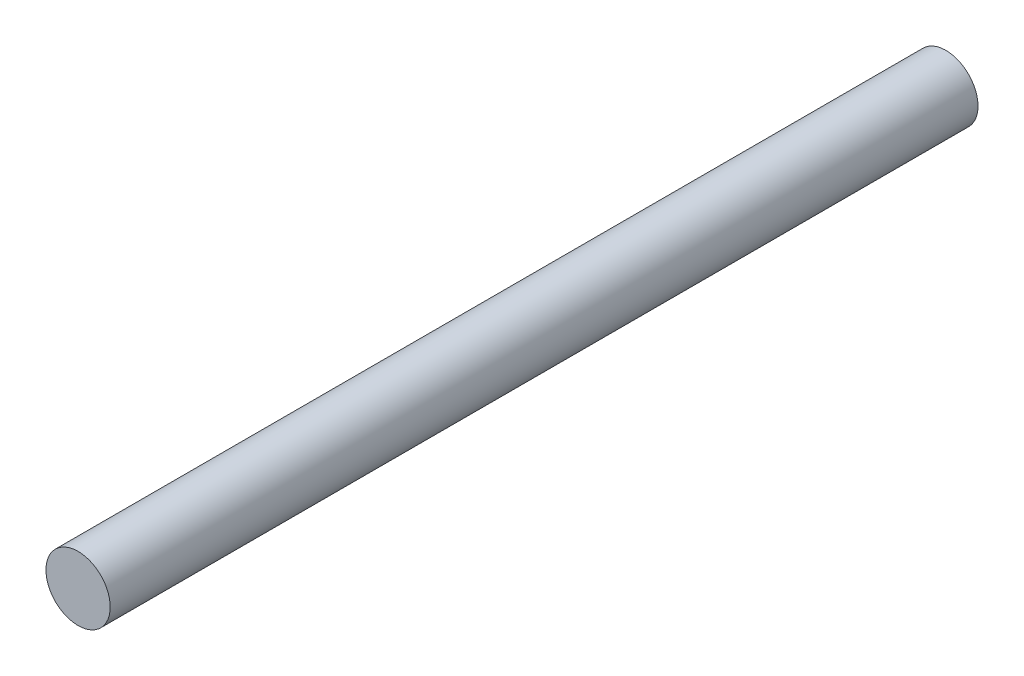
SolidWorks part; units mm, degrees
ref_plane "Front Plane" through (0, 0, 0) normal (0, 0, 1) x (1, 0, 0)
ref_plane "Top Plane" through (0, 0, 0) normal (0, 1, 0) x (1, 0, 0)
ref_plane "Right Plane" through (0, 0, 0) normal (1, 0, 0) x (0, 0, -1)
sketch "Sketch1" plane through (0, 0, 0) normal (0, 0, 1) x (1, 0, 0)
  circle A0 centre (0, 0) radius 5
  dimension "D1" = 10
extrude "Boss-Extrude1" add sketch "Sketch1" along normal mid plane 135
